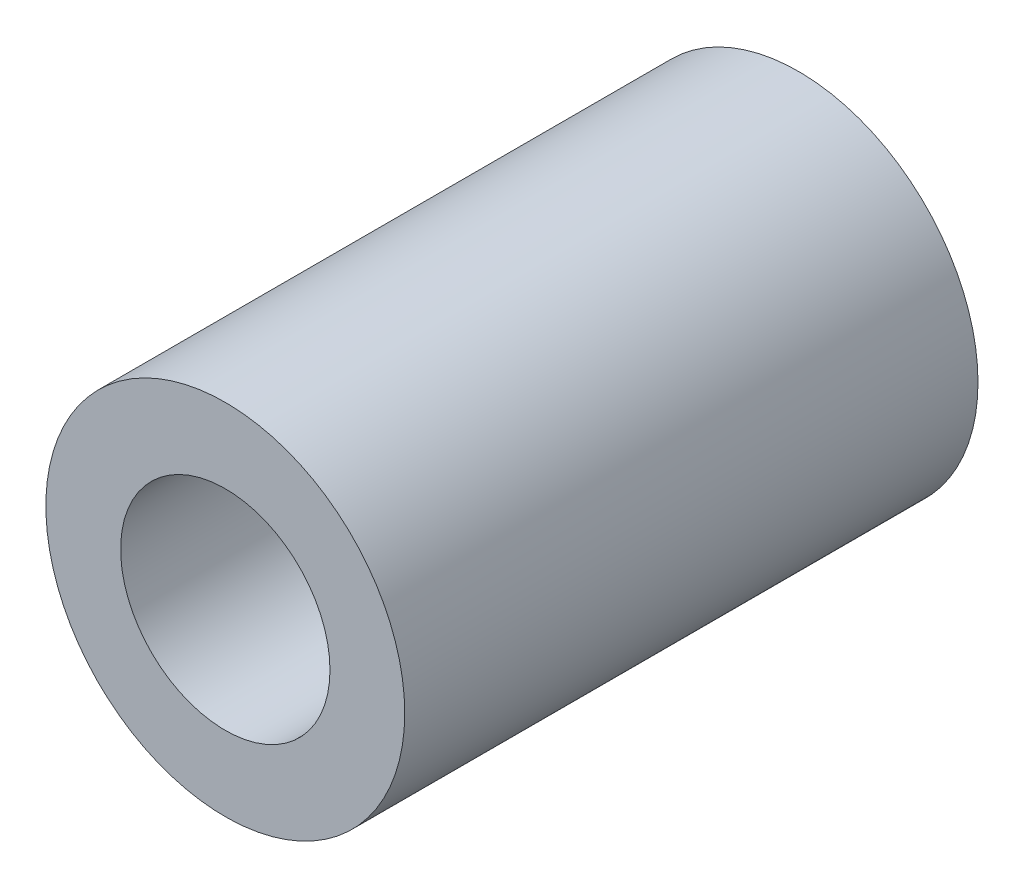
SolidWorks part; units mm, degrees
ref_plane "Plan de face" through (0, 0, 0) normal (0, 0, 1) x (1, 0, 0)
ref_plane "Plan de dessus" through (0, 0, 0) normal (0, 1, 0) x (1, 0, 0)
ref_plane "Plan de droite" through (0, 0, 0) normal (1, 0, 0) x (0, 0, -1)
sketch "Esquisse1" plane through (0, 0, 0) normal (0, 0, 1) x (1, 0, 0)
  circle A0 centre (0, 0) radius 3.6
  circle A1 centre (0, 0) radius 2.1
  dimension "D1" = 4.2
  dimension "D2" = 7.2
extrude "Boss.-Extru.1" add sketch "Esquisse1" along normal blind 11.5
